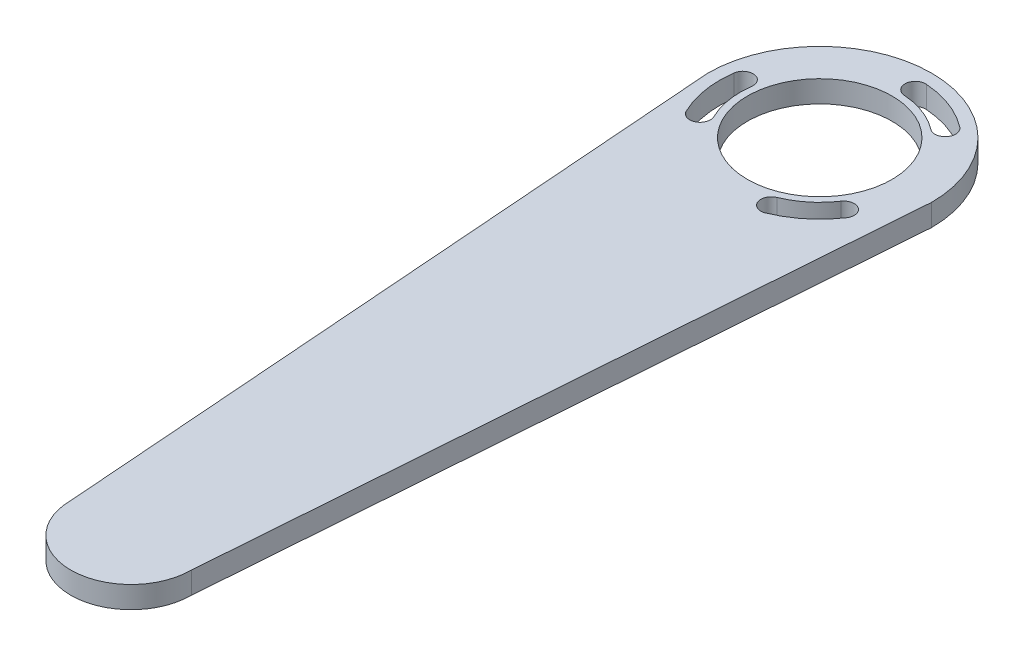
SolidWorks part; units mm, degrees
ref_plane "Front Plane" through (0, 0, 0) normal (0, 0, 1) x (1, 0, 0)
ref_plane "Top Plane" through (0, 0, 0) normal (0, 1, 0) x (1, 0, 0)
ref_plane "Right Plane" through (0, 0, 0) normal (1, 0, 0) x (0, 0, -1)
sketch "Sketch1" plane through (0, 0, 0) normal (0, 1, 0) x (1, 0, 0)
  line L0 (-32.5, 0) -> (-17.5, -200)
  line L2 (17.5, -200) -> (32.5, 0)
  circle A0 centre (0, 0) radius 32.5
  circle A1 centre (0, -200) radius 17.5
  dimension "D1" = 65
  dimension "D2" = 35
  dimension "D3" = 200
extrude "Boss-Extrude1" add sketch "Sketch1" along normal mid plane 6.35 contours L2 A0 L0 | A1 L2 A0 L0 | A1
sketch "Sketch2" plane through (0, 3.175, 0) normal (0, 1, 0) x (1, 0, 0)
  circle A0 centre (0, 0) radius 21
  dimension "D1" = 42
extrude "Cut-Extrude1" cut sketch "Sketch2" against normal through all
sketch "Sketch4" plane through (0, -3.175, 0) normal (0, -1, 0) x (1, 0, 0)
  arc A0 (14.0192, -18.2336) -> (1.6139, -22.9433) centre (0, 0) cw
  arc A1 (1.6139, -22.9433) -> (14.0192, -18.2336) centre (0, 0) ccw construction
  arc A2 (1.6139, -22.9433) -> (2.0349, -28.9285) centre (1.8244, -25.9359) ccw
  arc A3 (2.0349, -28.9285) -> (17.6763, -22.9902) centre (0, 0) ccw
  arc A4 (2.0349, -28.9285) -> (17.6763, -22.9902) centre (0, 0) ccw construction
  arc A5 (14.0192, -18.2336) -> (17.6763, -22.9902) centre (15.8477, -20.6119) cw
  arc A6 (1.6139, -22.9433) -> (2.0349, -28.9285) centre (1.8244, -25.9359) ccw construction
extrude "Cut-Extrude2" cut sketch "Sketch4" against normal through all
pattern_circular "CirPattern1" count 3 over 240 about axis through (0, 0, 0) along (0, 1, 0) of "Cut-Extrude2"
